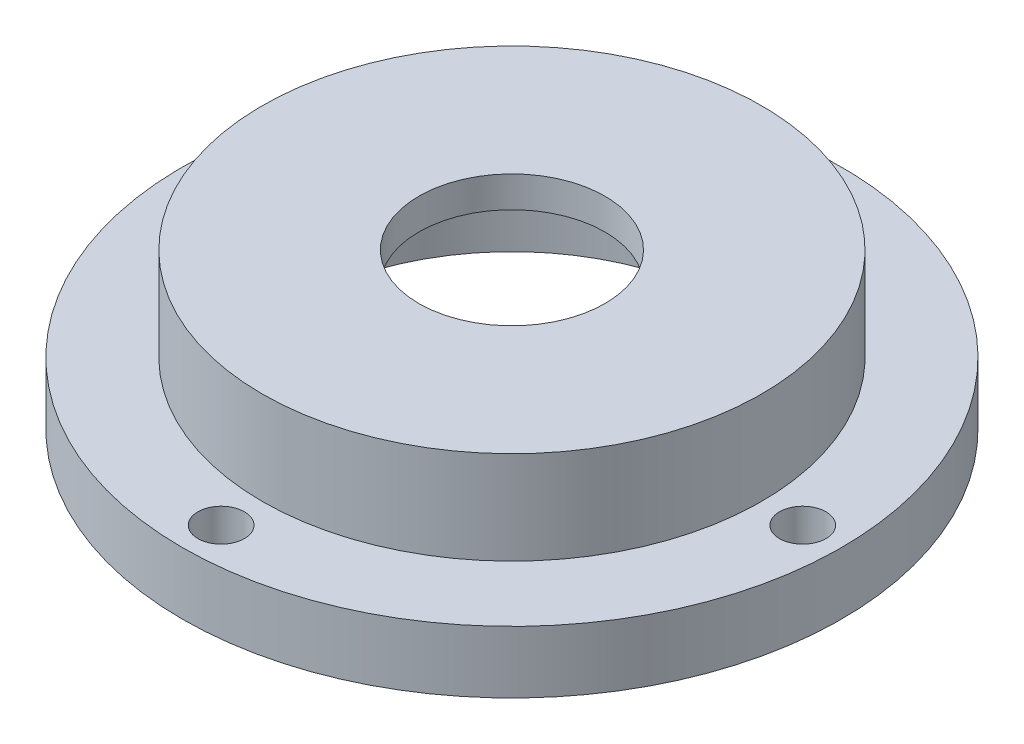
SolidWorks part; units mm, degrees
ref_plane "Спереди" through (0, 0, 0) normal (0, 0, 1) x (1, 0, 0)
ref_plane "Сверху" through (0, 0, 0) normal (0, 1, 0) x (1, 0, 0)
ref_plane "Справа" through (0, 0, 0) normal (1, 0, 0) x (0, 0, -1)
sketch "Эскиз1" plane through (0, 0, 0) normal (0, 1, 0) x (1, 0, 0)
  circle A1 centre (0, 0) radius 21.25
extrude "Вытянуть1" add sketch "Эскиз1" along normal blind 4
sketch "Эскиз2" plane through (0, 4, 0) normal (0, 1, 0) x (-1, 0, 0)
  circle A0 centre (0, 0) radius 16.1
extrude "Вытянуть2" add sketch "Эскиз2" along normal blind 6
sketch "Эскиз3" plane through (0, 0, 0) normal (0, -1, 0) x (1, 0, 0)
  circle A0 centre (0, 0) radius 14
extrude "Вытянуть3" cut sketch "Эскиз3" against normal blind 8
sketch "Эскиз4" plane through (0, 10, 0) normal (0, 1, 0) x (1, 0, 0)
  circle A0 centre (0, 0) radius 6
extrude "Вытянуть4" cut sketch "Эскиз4" against normal through all
sketch "Эскиз5" plane through (0, 4, 0) normal (0, 1, 0) x (1, 0, 0)
  circle A0 centre (0, 18.75) radius 1.5
  circle A1 centre (18.75, 0) radius 1.5
  circle A2 centre (0, -18.75) radius 1.5
  circle A3 centre (-18.75, 0) radius 1.5
  dimension "D1" = 18.75
extrude "Вытянуть5" cut sketch "Эскиз5" against normal blind 10
